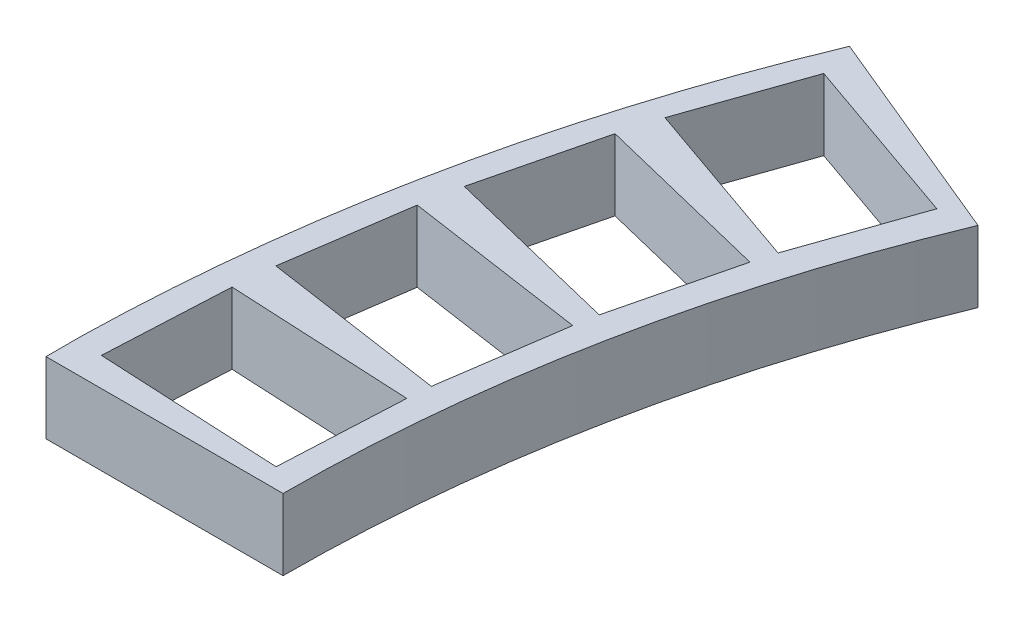
SolidWorks part; units mm, degrees
ref_plane "Front Plane" through (0, 0, 0) normal (0, 0, 1) x (1, 0, 0)
ref_plane "Top Plane" through (0, 0, 0) normal (0, 1, 0) x (1, 0, 0)
ref_plane "Right Plane" through (0, 0, 0) normal (1, 0, 0) x (0, 0, -1)
sketch "Sketch1" plane through (0, 0, 0) normal (0, 1, 0) x (1, 0, 0)
  line L0 (0, -1585.8629) -> (0, 77707.2829) construction
  line L1 (-1585.8629, 0) -> (77707.2829, 0) construction
  line L3 (-272.7199, 112.9643) -> (-235.7647, 97.6569)
  line L38 (-235.7647, 97.6569) -> (0, 0) construction
  line L58 (-295.1278, 6.0543) -> (-295.1278, 0)
  line L64 (-295.1278, 0) -> (-255.1898, 0)
  line L66 (-249.615, 73.0843) -> (-254.6156, 52.6884)
  line L67 (-254.6156, 52.6884) -> (-284.7239, 60.0701)
  line L91 (-241.6583, 96.6151) -> (-248.5803, 76.7888)
  line L92 (-248.5803, 76.7888) -> (-277.8479, 87.007)
  line L93 (-277.8479, 87.007) -> (-270.9258, 106.8334)
  line L94 (-270.9258, 106.8334) -> (-241.6583, 96.6151)
  line L95 (-284.7239, 60.0701) -> (-279.7233, 80.4661)
  line L96 (-279.7233, 80.4661) -> (-249.615, 73.0843)
  line L97 (-255.2924, 48.9021) -> (-258.3259, 28.1224)
  line L98 (-258.3259, 28.1224) -> (-289.0008, 32.6005)
  line L99 (-289.0008, 32.6005) -> (-285.9672, 53.3803)
  line L100 (-285.9672, 53.3803) -> (-255.2924, 48.9021)
  line L101 (-258.6388, 24.2889) -> (-259.6777, 3.3146)
  line L102 (-259.6777, 3.3146) -> (-290.6397, 4.8483)
  line L103 (-290.6397, 4.8483) -> (-289.6008, 25.8226)
  line L104 (-289.6008, 25.8226) -> (-258.6388, 24.2889)
  arc A1 (-295.1278, 6.0543) -> (-272.7199, 112.9643) centre (0, 0) cw
  arc A3 (-235.7647, 97.6569) -> (-255.1898, 0) centre (0, 0) ccw
  arc A59 (-202.2632, 163.0099) -> (-214.7699, 146.1385) centre (0, 0) ccw construction
  arc A60 (-202.2632, 163.0099) -> (-214.7699, 146.1385) centre (0, 0) ccw construction
  arc A61 (-202.2632, 163.0099) -> (-214.7699, 146.1385) centre (0, 0) ccw construction
  arc A62 (-202.2632, 163.0099) -> (-214.7699, 146.1385) centre (0, 0) ccw construction
  point P15 (-258.6388, 24.2889)
  point P34 (-258.3259, 28.1224)
  point P35 (-258.6388, 24.2889)
  point P36 (-258.3259, 28.1224)
  dimension "D1" = 22.5
  dimension "D7" = 4
extrude "Boss-Extrude1" add sketch "Sketch1" along normal blind 12
